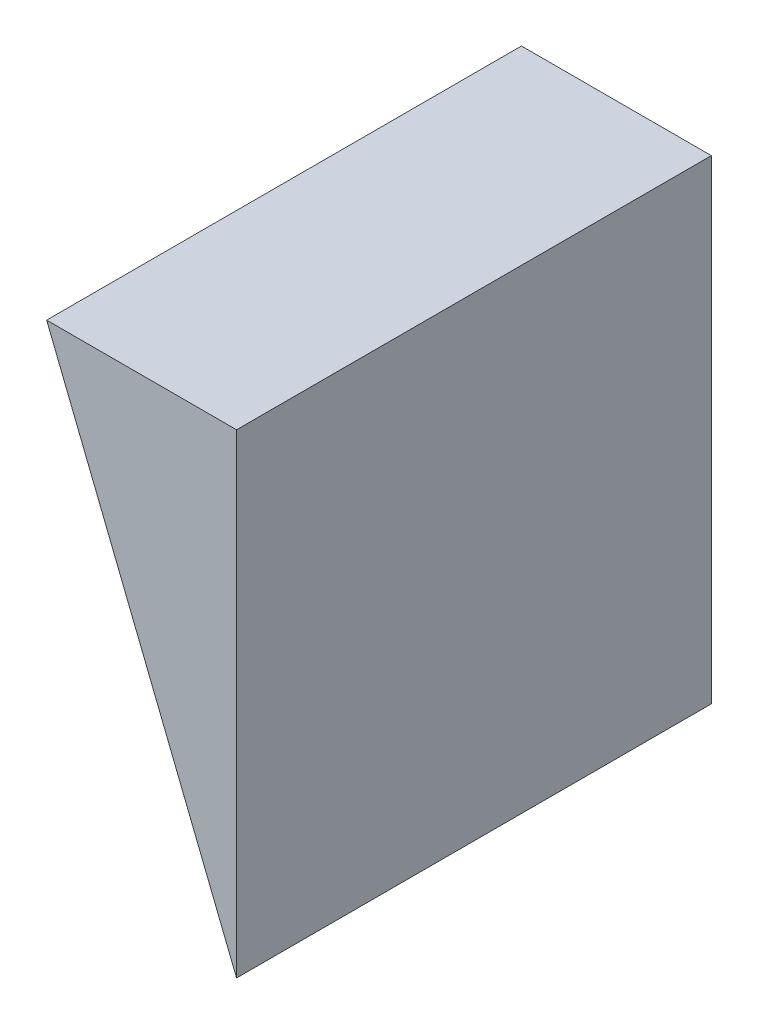
SolidWorks part; units mm, degrees
ref_plane "Front Plane" through (0, 0, 0) normal (0, 0, 1) x (1, 0, 0)
ref_plane "Top Plane" through (0, 0, 0) normal (0, 1, 0) x (1, 0, 0)
ref_plane "Right Plane" through (0, 0, 0) normal (1, 0, 0) x (0, 0, -1)
sketch "Sketch1" plane through (0, 0, 0) normal (0, 0, 1) x (1, 0, 0)
  line L0 (0, 0) -> (0, -5)
  line L1 (0, -5) -> (-2, 0)
  line L2 (-2, 0) -> (0, 0)
  dimension "D1" = 2
  dimension "D2" = 5
extrude "Boss-Extrude1" add sketch "Sketch1" along normal blind 5
